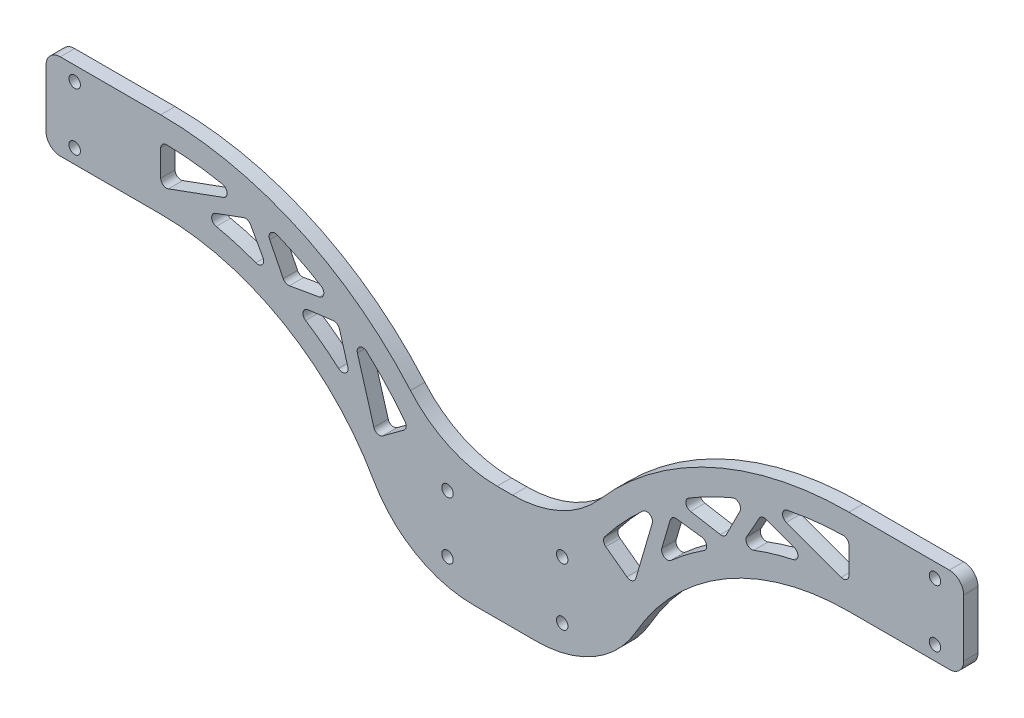
SolidWorks part; units mm, degrees
ref_plane "Plan de face" through (0, 0, 0) normal (0, 0, 1) x (1, 0, 0)
ref_plane "Plan de dessus" through (0, 0, 0) normal (0, 1, 0) x (1, 0, 0)
ref_plane "Plan de droite" through (0, 0, 0) normal (1, 0, 0) x (0, 0, -1)
sketch "Esquisse1" plane through (0, 0, 0) normal (0, 0, 1) x (1, 0, 0)
  line L0 (-37.5, 0) -> (37.5, 0)
  line L1 (0, 20) -> (37.5, 20) construction
  line L2 (160, 129.0542) -> (160, -74.83) construction
  line L3 (0, 62.4131) -> (0, -5.9928) construction
  line L4 (-160, 129.0542) -> (-160, -74.83) construction
  line L5 (160, 93.5) -> (160, 63.5)
  line L6 (160, 63.5) -> (120, 63.5)
  line L7 (22.6378, 40) -> (120, 93.5) construction
  line L8 (120, 93.5) -> (160, 93.5)
  line L9 (-22.6378, 40) -> (22.6378, 40)
  line L10 (120, 63.5) -> (37.5, 0) construction
  line L11 (-120, 63.5) -> (-37.5, 0) construction
  line L12 (-160, 63.5) -> (-120, 63.5)
  line L13 (-160, 93.5) -> (-160, 63.5)
  line L14 (-120, 93.5) -> (-160, 93.5)
  line L15 (-22.6378, 40) -> (-120, 93.5) construction
  line L16 (150, 93.5) -> (150, 63.5) construction
  line L17 (160, 78.5) -> (142.5512, 78.5) construction
  line L18 (120, 85.5) -> (120, 71.5)
  line L19 (44.8692, 33.5488) -> (33.6007, 41.8566)
  line L20 (44.8692, 33.5488) -> (60.5288, 54.7889) construction
  line L21 (84.2745, 79.3805) -> (91.9124, 81.7601) construction
  line L22 (74.3823, 59.5937) -> (81.523, 63.2007) construction
  line L23 (81.523, 63.2007) -> (107.9766, 70.7224) construction
  line L24 (44.8692, 33.5488) -> (53.2787, 62.2448)
  line L25 (52.63, 42.7649) -> (59.7264, 66.9804) construction
  line L26 (74.3823, 59.5937) -> (53.2787, 62.2448) construction
  line L27 (59.7264, 66.9804) -> (81.523, 63.2007) construction
  line L28 (107.9766, 70.7224) -> (84.2745, 79.3805) construction
  line L29 (81.523, 63.2007) -> (91.9124, 81.7601) construction
  line L30 (84.2745, 79.3805) -> (59.7264, 66.9804) construction
  line L31 (77.914, 61.4737) -> (71.6017, 73.9699) construction
  line L32 (84.2745, 79.3805) -> (74.3823, 59.5937) construction
  line L33 (120, 71.5) -> (91.9124, 81.7601)
  line L34 (52.63, 42.7649) -> (58.159, 61.6317)
  line L35 (58.159, 61.6317) -> (74.3823, 59.5937)
  line L36 (59.7264, 66.9804) -> (76.6114, 64.0524)
  line L37 (76.6114, 64.0524) -> (84.2745, 79.3805)
  line L38 (81.523, 63.2007) -> (89.5098, 77.4681)
  line L39 (89.5098, 77.4681) -> (107.9766, 70.7224)
  line L40 (-120, 85.5) -> (-120, 71.5)
  line L41 (-120, 71.5) -> (-91.9124, 81.7601)
  line L42 (-89.5098, 77.4681) -> (-107.9766, 70.7224)
  line L43 (-81.523, 63.2007) -> (-89.5098, 77.4681)
  line L44 (-76.6114, 64.0524) -> (-84.2745, 79.3805)
  line L45 (-59.7264, 66.9804) -> (-76.6114, 64.0524)
  line L46 (-58.159, 61.6317) -> (-74.3823, 59.5937)
  line L47 (-52.63, 42.7649) -> (-58.159, 61.6317)
  line L48 (-44.8692, 33.5488) -> (-33.6007, 41.8566)
  line L49 (-44.8692, 33.5488) -> (-53.2787, 62.2448)
  circle A0 centre (20, 30) radius 2
  circle A1 centre (-20, 30) radius 2
  circle A2 centre (-20, 10) radius 2
  circle A3 centre (20, 10) radius 2
  circle A4 centre (150, 88.5) radius 2
  circle A5 centre (150, 68.5) radius 2
  circle A6 centre (-150, 88.5) radius 2
  circle A7 centre (-150, 68.5) radius 2
  arc A8 (120, 93.5) -> (22.6378, 40) centre (120, -21.8425) ccw
  arc A9 (120, 63.5) -> (37.5, 0) centre (120, -21.8425) ccw
  arc A10 (-120, 63.5) -> (-37.5, 0) centre (-120, -21.8425) cw
  arc A11 (-120, 93.5) -> (-22.6378, 40) centre (-120, -21.8425) cw
  arc A12 (33.6007, 41.8566) -> (120, 85.5) centre (120, -21.8425) cw construction
  arc A13 (44.8692, 33.5488) -> (120, 71.5) centre (120, -21.8425) cw construction
  arc A14 (33.6007, 41.8566) -> (53.2787, 62.2448) centre (120, -21.8425) cw
  arc A15 (84.2745, 79.3805) -> (59.7264, 66.9804) centre (120, -21.8425) ccw
  arc A16 (120, 85.5) -> (91.9124, 81.7601) centre (120, -21.8425) ccw
  arc A17 (52.63, 42.7649) -> (74.3823, 59.5937) centre (120, -21.8425) cw
  arc A18 (107.9766, 70.7224) -> (81.523, 63.2007) centre (120, -21.8425) ccw
  arc A19 (-120, 85.5) -> (-91.9124, 81.7601) centre (-120, -21.8425) cw
  arc A20 (-107.9766, 70.7224) -> (-81.523, 63.2007) centre (-120, -21.8425) cw
  arc A21 (-84.2745, 79.3805) -> (-59.7264, 66.9804) centre (-120, -21.8425) cw
  arc A22 (-52.63, 42.7649) -> (-74.3823, 59.5937) centre (-120, -21.8425) ccw
  arc A23 (-33.6007, 41.8566) -> (-53.2787, 62.2448) centre (-120, -21.8425) ccw
  point P8 (0, 40)
  point P26 (0, 0)
  point P79 (71.6017, 73.9699)
  dimension "D5" = 58.5
  dimension "D10" = 4
  dimension "D3" = 320
  dimension "D6" = 4
  dimension "D14" = 8
  dimension "D15" = 8
  dimension "D1" = 40
  dimension "D2" = 75
  dimension "D4" = 10
  dimension "D7" = 5
  dimension "D8" = 30
  dimension "D9" = 120
  dimension "D11" = 40
  dimension "D12" = 20
  dimension "D13" = 20
  dimension "D16" = 8
  dimension "D17" = 8
extrude "Boss.-Extru.1" add sketch "Esquisse1" along normal blind 5
fillet "Congé1" radius 5 4 edges at (-160, 63.5, 2.5) (-160, 93.5, 2.5) (160, 63.5, 2.5) (160, 93.5, 2.5)
fillet "Congé2" radius 40 4 edges at (-37.5, 0, 2.5) (37.5, 0, 2.5) (22.6378, 40, 2.5) (-22.6378, 40, 2.5)
fillet "Congé3" radius 2 30 edges at (-44.8692, 33.5488, 2.5) (-33.6007, 41.8566, 2.5) (-53.2787, 62.2448, 2.5) (-52.63, 42.7649, 2.5) (-58.159, 61.6317, 2.5) (-74.3823, 59.5937, 2.5) (-59.7264, 66.9804, 2.5) (-76.6114, 64.0524, 2.5) (-81.523, 63.2007, 2.5) (-107.9766, 70.7224, 2.5) (-91.9124, 81.7601, 2.5) (-89.5098, 77.4681, 2.5) (-84.2745, 79.3805, 2.5) (-120, 71.5, 2.5) (-120, 85.5, 2.5) (120, 71.5, 2.5) (120, 85.5, 2.5) (91.9124, 81.7601, 2.5) (107.9766, 70.7224, 2.5) (58.159, 61.6317, 2.5) (59.7264, 66.9804, 2.5) (84.2745, 79.3805, 2.5) (89.5098, 77.4681, 2.5) (81.523, 63.2007, 2.5) (76.6114, 64.0524, 2.5) (74.3823, 59.5937, 2.5) (52.63, 42.7649, 2.5) (53.2787, 62.2448, 2.5) (44.8692, 33.5488, 2.5) (33.6007, 41.8566, 2.5)
equation "\"D\"= 12"
